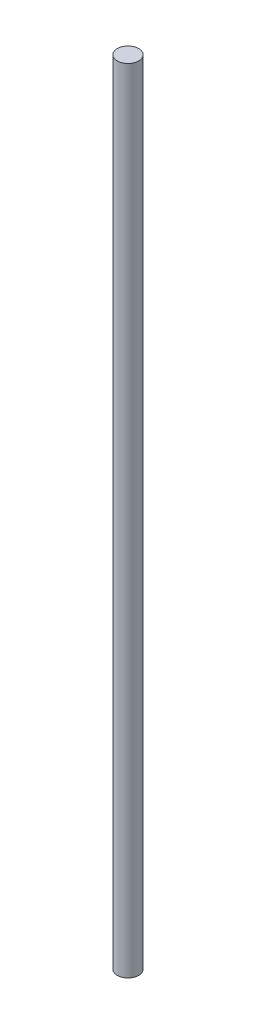
SolidWorks part; units mm, degrees
material "Alloy Steel"
ref_plane "Front" through (0, 0, 0) normal (0, 0, 1) x (1, 0, 0)
ref_plane "Top" through (0, 0, 0) normal (0, 1, 0) x (1, 0, 0)
ref_plane "Right" through (0, 0, 0) normal (1, 0, 0) x (0, 0, -1)
sketch "Sketch1" plane through (0, 0, 0) normal (0, 0, 1) x (1, 0, 0)
  line L0 (0, 92.25) -> (0, -92.25)
  line L1 (-2.5, -92.25) -> (2.5, -92.25)
  line L2 (-2.5, -92.25) -> (-2.5, 92.25)
  line L3 (-2.5, 92.25) -> (2.5, 92.25)
  line L4 (2.5, -92.25) -> (2.5, 92.25)
  line L5 (-2.5, -92.25) -> (2.5, 92.25) construction
  line L6 (-2.5, 92.25) -> (2.5, -92.25) construction
  line L7 (0, 90.75) -> (1, 90.75)
  line L8 (1, 90.75) -> (1, -90.75)
  line L9 (1, -90.75) -> (0, -90.75)
  point P0 (0, 0)
  dimension "D1" = 5
  dimension "D2" = 184.5
  dimension "D3" = 1.5
  dimension "D4" = 1.5
  dimension "D5" = 1.5
revolve "Revolve1" add sketch "Sketch1" angle 360 about L0
